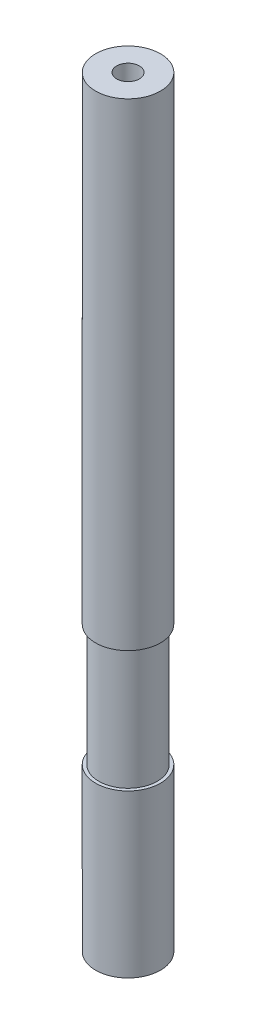
SolidWorks part; units mm, degrees
ref_plane "Front Plane" through (0, 0, 0) normal (0, 0, 1) x (1, 0, 0)
ref_plane "Top Plane" through (0, 0, 0) normal (0, 1, 0) x (1, 0, 0)
ref_plane "Right Plane" through (0, 0, 0) normal (1, 0, 0) x (0, 0, -1)
sketch "Sketch1" plane through (0, 0, 0) normal (0, 1, 0) x (1, 0, 0)
  circle A0 centre (0, 0) radius 4
  dimension "D1" = 8
extrude "Boss-Extrude1" add sketch "Sketch1" along normal mid plane 94
sketch "Sketch2" plane through (0, -47, 0) normal (0, -1, 0) x (1, 0, 0)
  circle A0 centre (0, 0) radius 1.4
  dimension "D1" = 2.8
extrude "Cut-Extrude1" cut sketch "Sketch2" against normal blind 10
mirror "Mirror1" about plane through (0, 0, 0) normal (0, 1, 0) of "Cut-Extrude1"
sketch "Sketch3" plane through (0, -47, 0) normal (0, -1, 0) x (1, 0, 0)
  circle A0 centre (0, 0) radius 3.6
  circle A1 centre (0, 0) radius 4
  circle A2 centre (0, 0) radius 4
  dimension "D1" = 0
  dimension "D2" = 0.4
extrude "Cut-Extrude2" cut sketch "Sketch3" against normal blind 15 from offset 20
